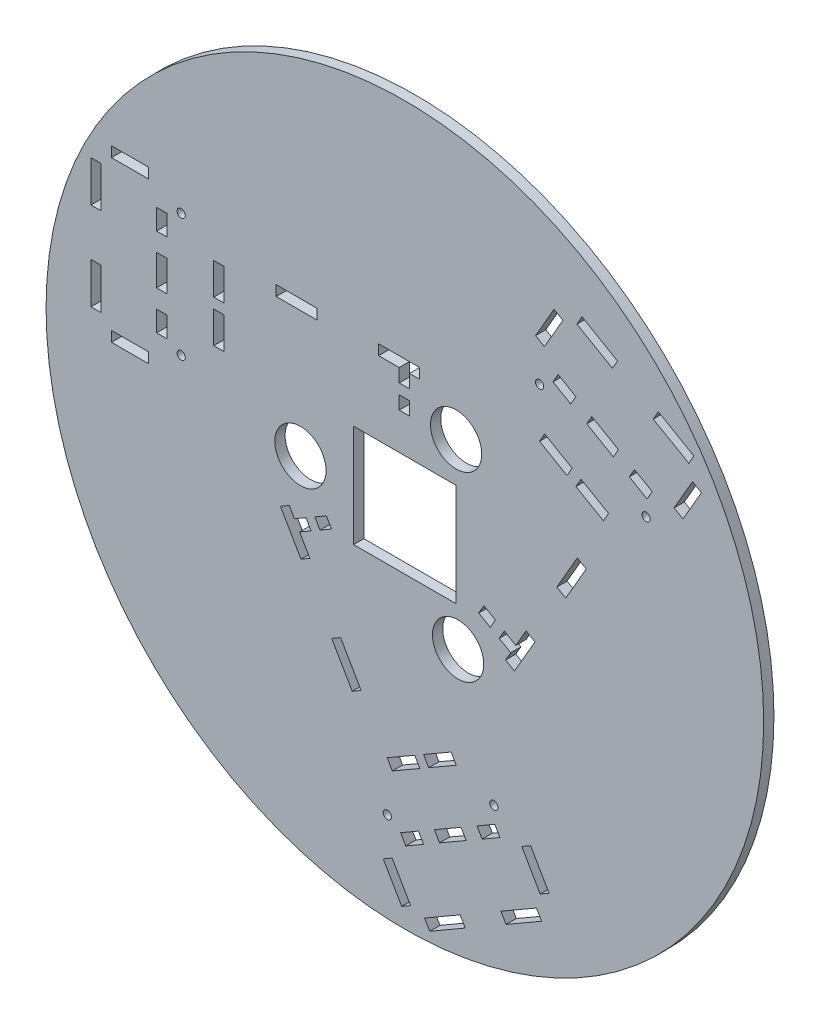
SolidWorks part; units mm, degrees
ref_plane "Plan de face" through (0, 0, 0) normal (0, 0, 1) x (1, 0, 0)
ref_plane "Plan de dessus" through (0, 0, 0) normal (0, 1, 0) x (1, 0, 0)
ref_plane "Plan de droite" through (0, 0, 0) normal (1, 0, 0) x (0, 0, -1)
sketch "Esquisse1" plane through (0, 0, 0) normal (0, 0, 1) x (1, 0, 0)
  circle A0 centre (148.0804, -12.1102) radius 175
  dimension "D1" = 350
extrude "Boss.-Extru.1" add sketch "Esquisse1" along normal blind 5
sketch "Esquisse2" plane through (0, 0, 5) normal (0, 0, 1) x (1, 0, 0)
  line L0 (135.3118, 53.7774) -> (135.3118, 48.7774)
  line L1 (5, 72.2774) -> (23, 72.2774)
  line L2 (5, 72.2774) -> (5, 67.2774)
  line L3 (5, 67.2774) -> (23, 67.2774)
  line L4 (23, 72.2774) -> (23, 67.2774)
  line L5 (-5, 62.2774) -> (0, 62.2774)
  line L6 (-5, 62.2774) -> (-5, 42.2774)
  line L7 (-5, 42.2774) -> (0, 42.2774)
  line L8 (0, 62.2774) -> (0, 42.2774)
  line L9 (-5, 19.2774) -> (0, 19.2774)
  line L10 (-5, 19.2774) -> (-5, -0.7226)
  line L11 (-5, -0.7226) -> (0, -0.7226)
  line L12 (0, 19.2774) -> (0, -0.7226)
  line L13 (5, -5.7226) -> (23, -5.7226)
  line L14 (5, -5.7226) -> (5, -10.7226)
  line L15 (5, -10.7226) -> (23, -10.7226)
  line L16 (23, -5.7226) -> (23, -10.7226)
  line L17 (27, 14.2774) -> (32, 14.2774)
  line L18 (27, 14.2774) -> (27, 4.2774)
  line L19 (27, 4.2774) -> (32, 4.2774)
  line L20 (32, 14.2774) -> (32, 4.2774)
  line L21 (27, 38.2774) -> (32, 38.2774)
  line L22 (27, 38.2774) -> (27, 23.2774)
  line L23 (27, 23.2774) -> (32, 23.2774)
  line L24 (32, 38.2774) -> (32, 23.2774)
  line L25 (27, 57.2774) -> (32, 57.2774)
  line L26 (27, 57.2774) -> (27, 47.2774)
  line L27 (27, 47.2774) -> (32, 47.2774)
  line L28 (32, 57.2774) -> (32, 47.2774)
  line L29 (54.86, 48.7774) -> (59.86, 48.7774)
  line L30 (54.86, 48.7774) -> (54.86, 33.2774)
  line L31 (54.86, 33.2774) -> (59.86, 33.2774)
  line L32 (59.86, 48.7774) -> (59.86, 33.2774)
  line L33 (54.86, 28.2774) -> (59.86, 28.2774)
  line L34 (54.86, 28.2774) -> (54.86, 12.7774)
  line L35 (54.86, 12.7774) -> (59.86, 12.7774)
  line L36 (59.86, 28.2774) -> (59.86, 12.7774)
  line L37 (85.3118, 53.7774) -> (105.3118, 53.7774)
  line L38 (85.3118, 53.7774) -> (85.3118, 48.7774)
  line L39 (85.3118, 48.7774) -> (105.3118, 48.7774)
  line L40 (105.3118, 53.7774) -> (105.3118, 48.7774)
  line L41 (145.3118, 37.2774) -> (150.3118, 37.2774)
  line L42 (145.3118, 37.2774) -> (145.3118, 30.7774)
  line L43 (145.3118, 30.7774) -> (150.3118, 30.7774)
  line L44 (150.3118, 37.2774) -> (150.3118, 30.7774)
  line L45 (135.3118, 48.7774) -> (145.3118, 48.7774)
  line L46 (155.3118, 48.7774) -> (135.3118, 48.7774) construction
  line L47 (145.3118, 48.7774) -> (145.3118, 42.2774)
  line L48 (145.3118, 42.2774) -> (150.3118, 42.2774)
  line L49 (150.3118, 42.2774) -> (150.3118, 48.7774)
  line L50 (150.3118, 48.7774) -> (155.3118, 48.7774)
  line L51 (155.3118, 48.7774) -> (155.3118, 53.7774)
  line L52 (155.3118, 53.7774) -> (135.3118, 53.7774)
  line L53 (292.7025, 69.6073) -> (283.7025, 54.0188)
  line L54 (292.7025, 69.6073) -> (288.3723, 72.1073)
  line L55 (288.3723, 72.1073) -> (279.3723, 56.5188)
  line L56 (283.7025, 54.0188) -> (279.3723, 56.5188)
  line L57 (289.0422, 83.2676) -> (286.5422, 78.9374)
  line L58 (289.0422, 83.2676) -> (271.7217, 93.2676)
  line L59 (271.7217, 93.2676) -> (269.2217, 88.9374)
  line L60 (286.5422, 78.9374) -> (269.2217, 88.9374)
  line L61 (251.8031, 104.7676) -> (249.3031, 100.4374)
  line L62 (251.8031, 104.7676) -> (234.4826, 114.7676)
  line L63 (234.4826, 114.7676) -> (231.9826, 110.4374)
  line L64 (249.3031, 100.4374) -> (231.9826, 110.4374)
  line L65 (225.1525, 108.6073) -> (216.1525, 93.0188)
  line L66 (225.1525, 108.6073) -> (220.8223, 111.1073)
  line L67 (220.8223, 111.1073) -> (211.8223, 95.5188)
  line L68 (216.1525, 93.0188) -> (211.8223, 95.5188)
  line L69 (231.473, 79.5547) -> (228.973, 75.2246)
  line L70 (231.473, 79.5547) -> (222.8127, 84.5547)
  line L71 (222.8127, 84.5547) -> (220.3127, 80.2246)
  line L72 (228.973, 75.2246) -> (220.3127, 80.2246)
  line L73 (252.2576, 67.5547) -> (249.7576, 63.2246)
  line L74 (252.2576, 67.5547) -> (239.2672, 75.0547)
  line L75 (239.2672, 75.0547) -> (236.7672, 70.7246)
  line L76 (249.7576, 63.2246) -> (236.7672, 70.7246)
  line L77 (268.7121, 58.0547) -> (266.2121, 53.7246)
  line L78 (268.7121, 58.0547) -> (260.0518, 63.0547)
  line L79 (260.0518, 63.0547) -> (257.5518, 58.7246)
  line L80 (266.2121, 53.7246) -> (257.5518, 58.7246)
  line L81 (247.4209, 38.1773) -> (244.9209, 33.8472)
  line L82 (247.4209, 38.1773) -> (233.9975, 45.9273)
  line L83 (233.9975, 45.9273) -> (231.4975, 41.5972)
  line L84 (244.9209, 33.8472) -> (231.4975, 41.5972)
  line L85 (229.6673, 48.4273) -> (227.1673, 44.0972)
  line L86 (229.6673, 48.4273) -> (216.2439, 56.1773)
  line L87 (216.2439, 56.1773) -> (213.7439, 51.8472)
  line L88 (227.1673, 44.0972) -> (213.7439, 51.8472)
  line L89 (211.5251, -33.996) -> (207.195, -31.496)
  line L90 (236.5251, 9.3053) -> (226.5251, -8.0153)
  line L91 (236.5251, 9.3053) -> (232.195, 11.8053)
  line L92 (232.195, 11.8053) -> (222.195, -5.5153)
  line L93 (226.5251, -8.0153) -> (222.195, -5.5153)
  line L94 (192.2357, -34.4063) -> (189.7357, -38.7364)
  line L95 (192.2357, -34.4063) -> (186.6065, -31.1563)
  line L96 (186.6065, -31.1563) -> (184.1065, -35.4864)
  line L97 (189.7357, -38.7364) -> (184.1065, -35.4864)
  line L98 (207.195, -31.496) -> (202.195, -40.1563)
  line L99 (202.195, -40.1563) -> (196.5658, -36.9063)
  line L100 (196.5658, -36.9063) -> (194.0658, -41.2364)
  line L101 (194.0658, -41.2364) -> (199.695, -44.4864)
  line L102 (199.695, -44.4864) -> (197.195, -48.8165)
  line L103 (197.195, -48.8165) -> (201.5251, -51.3165)
  line L104 (201.5251, -51.3165) -> (211.5251, -33.996)
  line L105 (146.5388, -178.2153) -> (137.5388, -162.6268)
  line L106 (146.5388, -178.2153) -> (150.869, -175.7153)
  line L107 (150.869, -175.7153) -> (141.869, -160.1268)
  line L108 (137.5388, -162.6268) -> (141.869, -160.1268)
  line L109 (160.1991, -181.8755) -> (157.6991, -177.5454)
  line L110 (160.1991, -181.8755) -> (177.5196, -171.8755)
  line L111 (177.5196, -171.8755) -> (175.0196, -167.5454)
  line L112 (157.6991, -177.5454) -> (175.0196, -167.5454)
  line L113 (197.4382, -160.3755) -> (194.9382, -156.0454)
  line L114 (197.4382, -160.3755) -> (214.7587, -150.3755)
  line L115 (214.7587, -150.3755) -> (212.2587, -146.0454)
  line L116 (194.9382, -156.0454) -> (212.2587, -146.0454)
  line L117 (214.0888, -139.2153) -> (205.0888, -123.6268)
  line L118 (214.0888, -139.2153) -> (218.4189, -136.7153)
  line L119 (218.4189, -136.7153) -> (209.4189, -121.1268)
  line L120 (205.0888, -123.6268) -> (209.4189, -121.1268)
  line L121 (185.7683, -130.1627) -> (183.2683, -125.8326)
  line L122 (185.7683, -130.1627) -> (194.4286, -125.1627)
  line L123 (194.4286, -125.1627) -> (191.9286, -120.8326)
  line L124 (183.2683, -125.8326) -> (191.9286, -120.8326)
  line L125 (164.9837, -142.1627) -> (162.4837, -137.8326)
  line L126 (164.9837, -142.1627) -> (177.9741, -134.6627)
  line L127 (177.9741, -134.6627) -> (175.4741, -130.3326)
  line L128 (162.4837, -137.8326) -> (175.4741, -130.3326)
  line L129 (148.5292, -151.6627) -> (146.0292, -147.3326)
  line L130 (148.5292, -151.6627) -> (157.1895, -146.6627)
  line L131 (157.1895, -146.6627) -> (154.6895, -142.3326)
  line L132 (146.0292, -147.3326) -> (154.6895, -142.3326)
  line L133 (141.9604, -123.2852) -> (139.4604, -118.9551)
  line L134 (141.9604, -123.2852) -> (155.3838, -115.5352)
  line L135 (155.3838, -115.5352) -> (152.8838, -111.2051)
  line L136 (139.4604, -118.9551) -> (152.8838, -111.2051)
  line L137 (159.7139, -113.0352) -> (157.2139, -108.7051)
  line L138 (159.7139, -113.0352) -> (173.1373, -105.2852)
  line L139 (173.1373, -105.2852) -> (170.6373, -100.9551)
  line L140 (157.2139, -108.7051) -> (170.6373, -100.9551)
  line L141 (97.4044, -56.1119) -> (101.7345, -53.6119)
  line L142 (122.4044, -99.4132) -> (112.4044, -82.0927)
  line L143 (122.4044, -99.4132) -> (126.7345, -96.9132)
  line L144 (126.7345, -96.9132) -> (116.7345, -79.5927)
  line L145 (112.4044, -82.0927) -> (116.7345, -79.5927)
  line L146 (106.6938, -39.2017) -> (104.1938, -34.8716)
  line L147 (106.6938, -39.2017) -> (112.323, -35.9517)
  line L148 (112.323, -35.9517) -> (109.823, -31.6216)
  line L149 (104.1938, -34.8716) -> (109.823, -31.6216)
  line L150 (101.7345, -53.6119) -> (96.7345, -44.9517)
  line L151 (96.7345, -44.9517) -> (102.3637, -41.7017)
  line L152 (102.3637, -41.7017) -> (99.8637, -37.3716)
  line L153 (99.8637, -37.3716) -> (94.2345, -40.6216)
  line L154 (94.2345, -40.6216) -> (91.7345, -36.2914)
  line L155 (91.7345, -36.2914) -> (87.4044, -38.7914)
  line L156 (87.4044, -38.7914) -> (97.4044, -56.1119)
  point P83 (148.0804, -12.1102)
  point P192 (148.0804, -12.1102)
  point P193 (148.0804, -12.1102)
  dimension "D1" = 3
extrude "Enlèv. mat.-Extru.1" cut sketch "Esquisse2" against normal blind 5
sketch "Esquisse6" plane through (0, 0, 5) normal (0, 0, 1) x (1, 0, 0)
  line L0 (93.9998, -7.2151) -> (100.2998, -18.127) construction
  line L2 (123.0804, -37.1102) -> (173.0804, -37.1102)
  line L3 (123.0804, -37.1102) -> (123.0804, 12.8898)
  line L4 (123.0804, 12.8898) -> (173.0804, 12.8898)
  line L5 (173.0804, -37.1102) -> (173.0804, 12.8898)
  line L6 (123.0804, -37.1102) -> (173.0804, 12.8898) construction
  line L7 (123.0804, 12.8898) -> (173.0804, -37.1102) construction
  circle A0 centre (173.06, 32.2774) radius 12.5
  circle A1 centre (174.0314, -55.9369) radius 12.5
  circle A2 centre (97.1498, -12.671) radius 12.5
  point P2 (148.0804, -12.1102)
  point P8 (148.0804, -12.1102)
  point P10 (148.0804, -12.1102)
  dimension "D2" = 25
  dimension "D3" = 50
  dimension "D4" = 50
  dimension "D1" = 3
extrude "Enlèv. mat.-Extru.6" cut sketch "Esquisse6" against normal blind 5
hole_wizard "Trous de centrage Ø4.0mm1" positions "Esquisse8" profile "Esquisse9" hole size "Ø4.0" standard "Ansi Metric" end condition through all
sketch "Esquisse8" plane through (148.0804, -12.1102, -78) normal (0, 0, -1) x (0.9999, -0.0106, 0)
  point P0 (64.7609, -88.7167)
  point P3 (117.0387, -59.2713)
  point P6 (-109.8498, -71.7228)
  point P9 (-109.2114, -11.7262)
  point P12 (-7.1889, 130.9941)
  point P15 (44.4505, 100.4429)
sketch "Esquisse9" plane through (213.7816, 75.9124, -78) normal (1, 0, 0) x (0, 1, 0)
  line L0 (0, 0) -> (0, 83)
  line L1 (0, 83) -> (2, 83)
  line L2 (2, 83) -> (2, 0)
  line L3 (2, 0) -> (0, 0)
  line L4 (0, -6.35) -> (0, 107.95) construction
  dimension "Diamètre du perçage jusqu'au prochain" = 4
  dimension "Profondeur du perçage jusqu'au prochain" = 83
